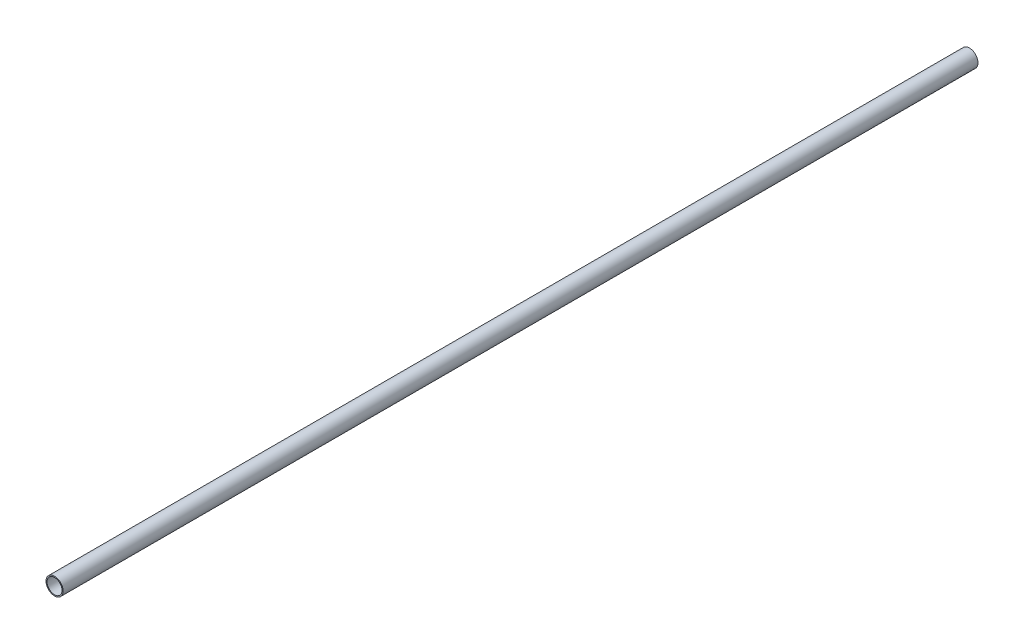
SolidWorks part; units mm, degrees
material "Poltrusion Carbon Fiber"
ref_plane "Front Plane" through (0, 0, 0) normal (0, 0, 1) x (1, 0, 0)
ref_plane "Top Plane" through (0, 0, 0) normal (0, 1, 0) x (1, 0, 0)
ref_plane "Right Plane" through (0, 0, 0) normal (1, 0, 0) x (0, 0, -1)
sketch "Эскиз1" plane through (0, 0, 0) normal (0, 0, 1) x (1, 0, 0)
  circle A0 centre (0, 0) radius 4
  circle A1 centre (0, 0) radius 3.5
  dimension "D1" = 8
  dimension "D2" = 0.5
extrude "Бобышка-Вытянуть1" add sketch "Эскиз1" along normal mid plane 427
